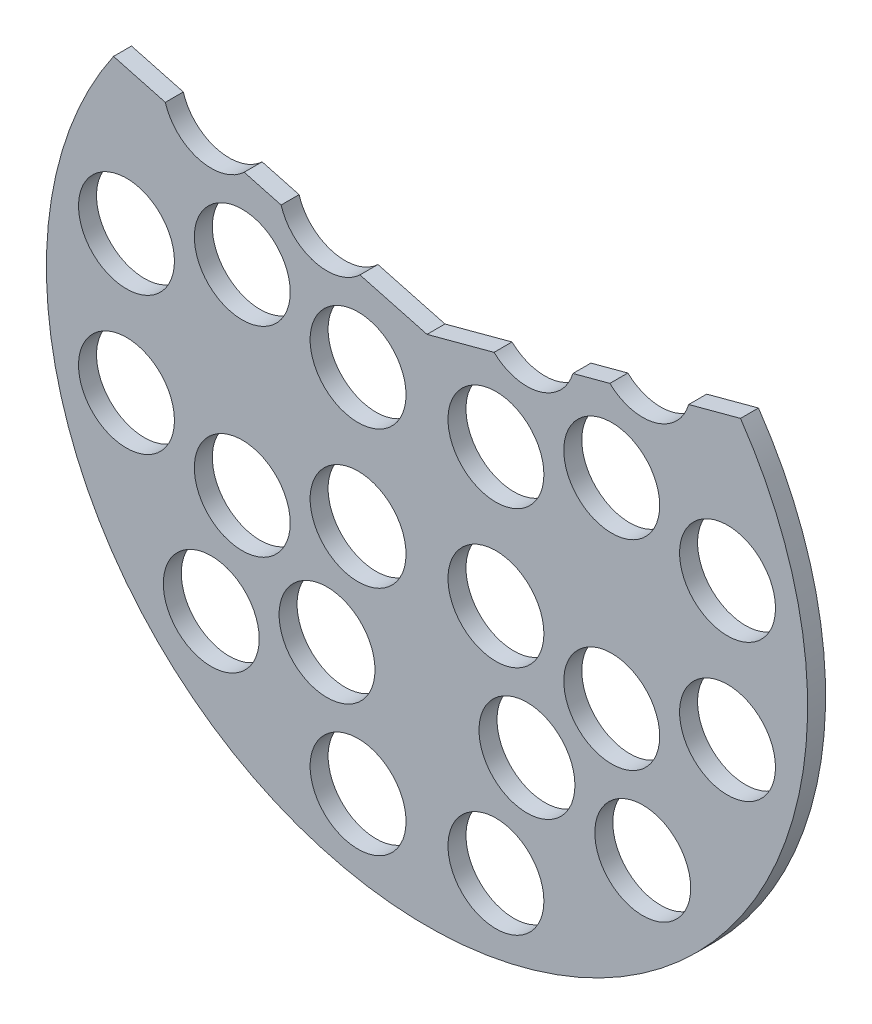
SolidWorks part; units mm, degrees
material "PPS"
ref_plane "Front Plane" through (0, 0, 0) normal (0, 0, 1) x (1, 0, 0)
ref_plane "Top Plane" through (0, 0, 0) normal (0, 1, 0) x (1, 0, 0)
ref_plane "Right Plane" through (0, 0, 0) normal (1, 0, 0) x (0, 0, -1)
sketch "Sketch1" plane through (0, 0, 0) normal (0, 0, 1) x (1, 0, 0)
  line L0 (0, 0) -> (-31.75, 0) construction
  line L1 (0, 0) -> (31.75, 0) construction
  line L2 (0, 0) -> (0, -31.75) construction
  line L3 (0, 0) -> (0, 31.75) construction
  line L4 (17.9974, 17.9974) -> (15.4093, 8.3382) construction
  line L5 (15.4093, 8.3382) -> (5.75, 5.75) construction
  line L6 (5.75, 5.75) -> (8.3382, 15.4093) construction
  line L7 (8.3382, 15.4093) -> (17.9974, 17.9974) construction
  line L8 (0, 0) -> (5.75, 5.75) construction
  line L9 (0, 0) -> (5.75, -5.75) construction
  line L10 (8.3382, 15.4093) -> (15.4093, 8.3382) construction
  line L11 (15.4093, 8.3382) -> (25.0685, 5.75) construction
  line L12 (5.75, 25.0685) -> (8.3382, 15.4093) construction
  circle A0 centre (0, 0) radius 31.75
  circle A1 centre (5.75, 5.75) radius 4
  circle A2 centre (8.3382, 15.4093) radius 4
  circle A3 centre (17.9974, 17.9974) radius 4
  circle A4 centre (15.4093, 8.3382) radius 4
  circle A5 centre (25.0685, 5.75) radius 4
  circle A6 centre (5.75, 25.0685) radius 4
  circle A7 centre (25.0686, -5.75) radius 4
  circle A8 centre (15.4093, -8.3382) radius 4
  circle A9 centre (17.9975, -17.9974) radius 4
  circle A10 centre (8.3382, -15.4092) radius 4
  circle A11 centre (5.75, -25.0685) radius 4
  circle A12 centre (5.75, -5.75) radius 4
  circle A13 centre (-5.7499, -25.0685) radius 4
  circle A14 centre (-8.3381, -15.4093) radius 4
  circle A15 centre (-17.9974, -17.9974) radius 4
  circle A16 centre (-15.4092, -8.3382) radius 4
  circle A17 centre (-25.0684, -5.75) radius 4
  circle A18 centre (-5.7499, -5.75) radius 4
  circle A19 centre (-25.0685, 5.75) radius 4
  circle A20 centre (-15.4092, 8.3382) radius 4
  circle A21 centre (-17.9974, 17.9974) radius 4
  circle A22 centre (-8.3382, 15.4092) radius 4
  circle A23 centre (-5.75, 25.0685) radius 4
  circle A24 centre (-5.75, 5.75) radius 4
  dimension "D1" = 63.5
  dimension "D2" = 8
  dimension "6" = 5.75
  dimension "D4" = 5.75
  dimension "D5" = 5.75
  dimension "D6" = 150
  dimension "D7" = 5.75
  dimension "D8" = 10
  dimension "D13" = 90
  dimension "D14" = 8.1317
  dimension "D12" = 4
extrude "Boss-Extrude1" add sketch "Sketch1" along normal blind 1.5
sketch "Sketch2" plane through (0, 0, 0) normal (0, 0, 1) x (1, 0, 0)
  line L0 (0, 35.9928) -> (0, 0) construction
  line L1 (-8.3382, 15.4092) -> (-17.9974, 17.9974) construction
  line L2 (8.3382, 15.4093) -> (17.9974, 17.9974) construction
  line L3 (-26.1499, 18.0068) -> (0, 11)
  line L4 (0, 11) -> (26.1499, 18.0068)
  circle A0 centre (0, 0) radius 31.75 construction
  arc A1 (26.1499, 18.0068) -> (-26.1499, 18.0068) centre (0, 0) ccw
  dimension "D1" = 11
extrude "Cut-Extrude1" cut sketch "Sketch2" along normal through all
